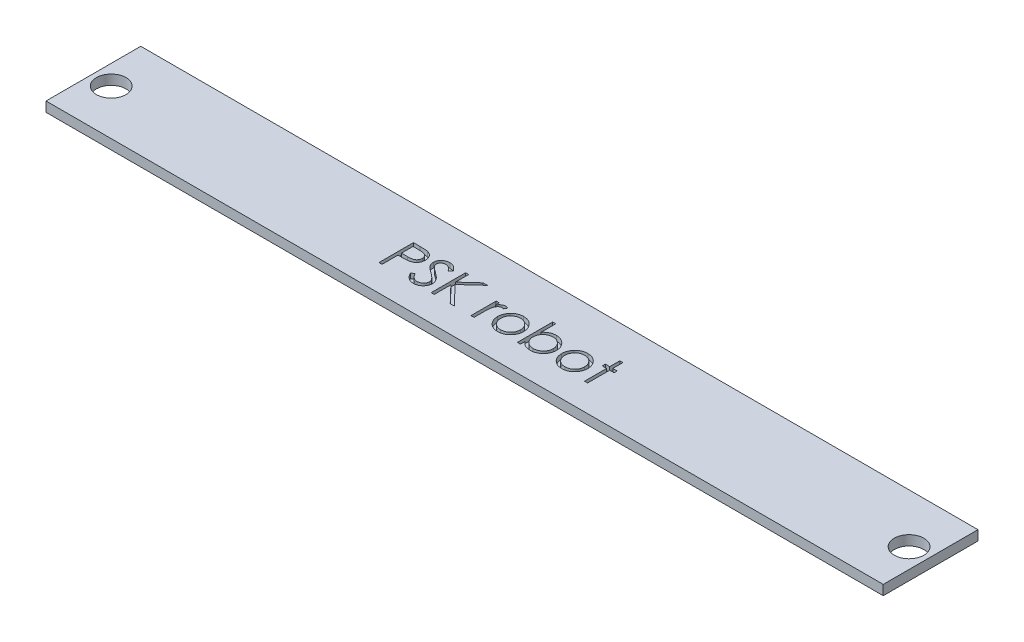
SolidWorks part; units mm, degrees
ref_plane "Front Plane" through (0, 0, 0) normal (0, 0, 1) x (1, 0, 0)
ref_plane "Top Plane" through (0, 0, 0) normal (0, 1, 0) x (1, 0, 0)
ref_plane "Right Plane" through (0, 0, 0) normal (1, 0, 0) x (0, 0, -1)
sketch "Sketch1" plane through (0, 0, 0) normal (0, 1, 0) x (1, 0, 0)
  line L1 (-42.5, 4.81) -> (42.5, 4.81)
  line L2 (-42.5, 4.81) -> (-42.5, -4.81)
  line L3 (-42.5, -4.81) -> (42.5, -4.81)
  line L4 (42.5, 4.81) -> (42.5, -4.81)
  line L5 (-42.5, 4.81) -> (42.5, -4.81) construction
  line L6 (-42.5, -4.81) -> (42.5, 4.81) construction
  circle A0 centre (-40.5, -0.19) radius 1.5
  circle A1 centre (40.5, -0.19) radius 1.5
  point P0 (0, 0)
  dimension "D3" = 3
  dimension "D5" = 3
  dimension "D6" = 5
  dimension "D7" = 2
  dimension "D1" = 85
  dimension "D2" = 9.62
  dimension "D4" = 2
extrude "Boss-Extrude1" add sketch "Sketch1" along normal blind 1
sketch "Sketch2" plane through (0, 1, 0) normal (0, 1, 0) x (1, 0, 0)
  text T0 "PSK robot"
extrude "Cut-Extrude1" cut sketch "Sketch2" against normal blind 0.5
